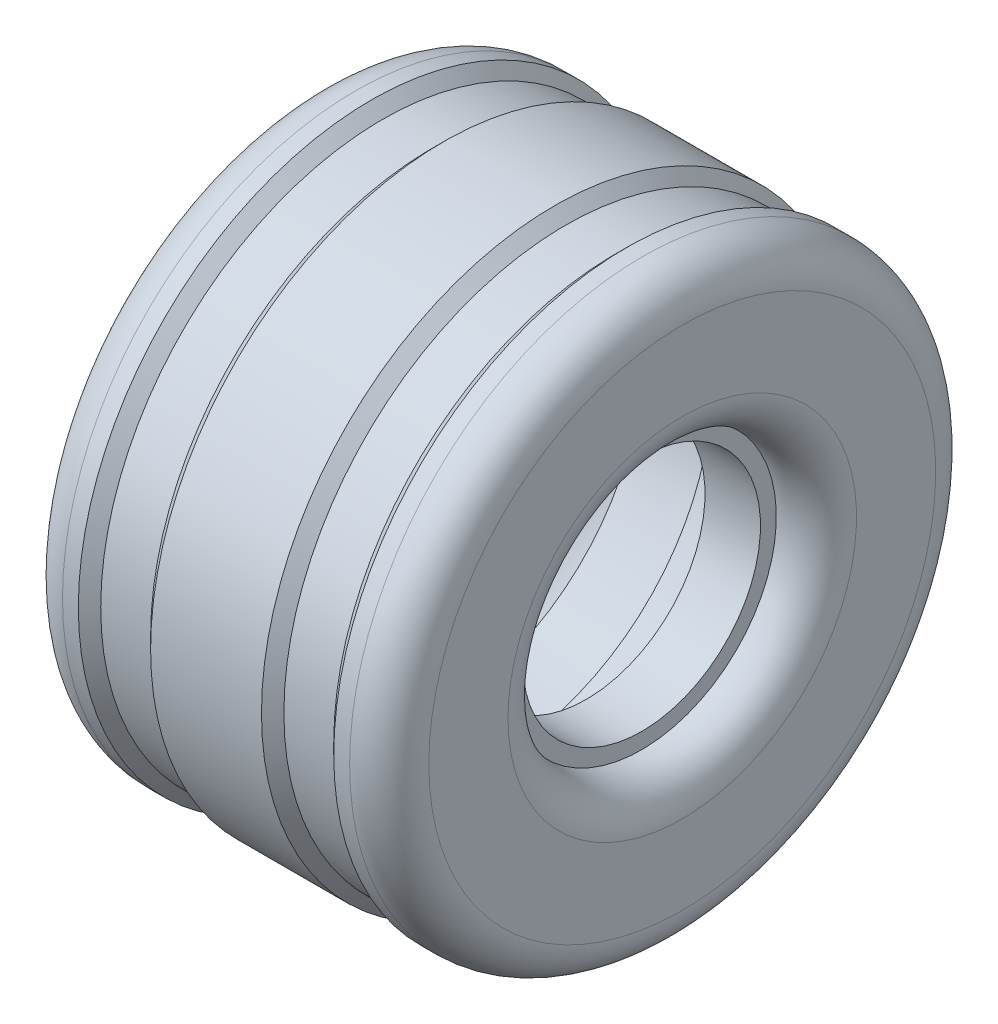
SolidWorks part; units mm, degrees
material "BUTYL"
ref_plane "Plan de face" through (0, 0, 0) normal (0, 0, 1) x (1, 0, 0)
ref_plane "Plan de dessus" through (0, 0, 0) normal (0, 1, 0) x (1, 0, 0)
ref_plane "Plan de droite" through (0, 0, 0) normal (1, 0, 0) x (0, 0, -1)
sketch "Esquisse1" plane through (0, 0, 0) normal (0, 0, 1) x (1, 0, 0)
  line L22 (0, 0) -> (180, 0) construction
  line L42 (180, 0) -> (180, 150) construction
  line L67 (18.7642, 369.9847) -> (32.9063, 355.8426)
  line L68 (250, 369.9847) -> (110, 369.9847)
  line L71 (-51.2358, 319.9847) -> (-51.2358, 219.9847)
  line L72 (32.9063, 355.8426) -> (95.8579, 355.8426)
  line L73 (95.8579, 355.8426) -> (110, 369.9847)
  line L75 (0, 170) -> (0, 150)
  line L76 (0, 150) -> (70, 150)
  line L77 (70, 150) -> (70, 170)
  line L78 (70, 170) -> (70, 220)
  line L79 (18.7642, 369.9847) -> (-1.2358, 369.9847)
  line L80 (180, 268.2789) -> (103.434, 257.2381)
  line L81 (180, 268.2789) -> (256.566, 257.2381)
  line L82 (341.2358, 369.9847) -> (361.2358, 369.9847)
  line L83 (290, 170) -> (290, 220)
  line L84 (290, 150) -> (290, 170)
  line L85 (360, 150) -> (290, 150)
  line L86 (360, 170) -> (360, 150)
  line L87 (264.1421, 355.8426) -> (250, 369.9847)
  line L88 (327.0937, 355.8426) -> (264.1421, 355.8426)
  line L89 (411.2358, 319.9847) -> (411.2358, 220.0004)
  line L90 (341.2358, 369.9847) -> (327.0937, 355.8426)
  arc A13 (-1.2358, 369.9847) -> (-51.2358, 319.9847) centre (-1.2358, 319.9847) ccw
  arc A14 (0, 170) -> (-51.2358, 219.9847) centre (-1.2358, 219.9847) cw
  arc A15 (360, 170) -> (411.2358, 220.0004) centre (361.2358, 219.9847) ccw
  arc A16 (361.2358, 369.9847) -> (411.2358, 319.9847) centre (361.2358, 319.9847) cw
  spline S0 degree 2 poles (70, 220) (64.755, 231.2039) (103.434, 257.2381) knots 0 0 0 0.545739 0.545739 0.545739
  spline S1 degree 2 poles (290, 220) (295.245, 231.2039) (256.566, 257.2381) knots 0 0 0 0.545739 0.545739 0.545739
  point P3 (411.2358, 369.9847)
  point P13 (-51.2358, 369.9847)
  point P37 (180, 369.9847)
  dimension "D3" = 100
  dimension "D5" = 70
  dimension "D11" = 70
  dimension "D12" = 20
  dimension "D9" = 50
  dimension "D10" = 50
  dimension "D1" = 180
  dimension "D2" = 150
  dimension "D6" = 45
  dimension "D7" = 45
  dimension "D8" = 20
revolve "Révolution1" add sketch "Esquisse1" angle 360 about L22
